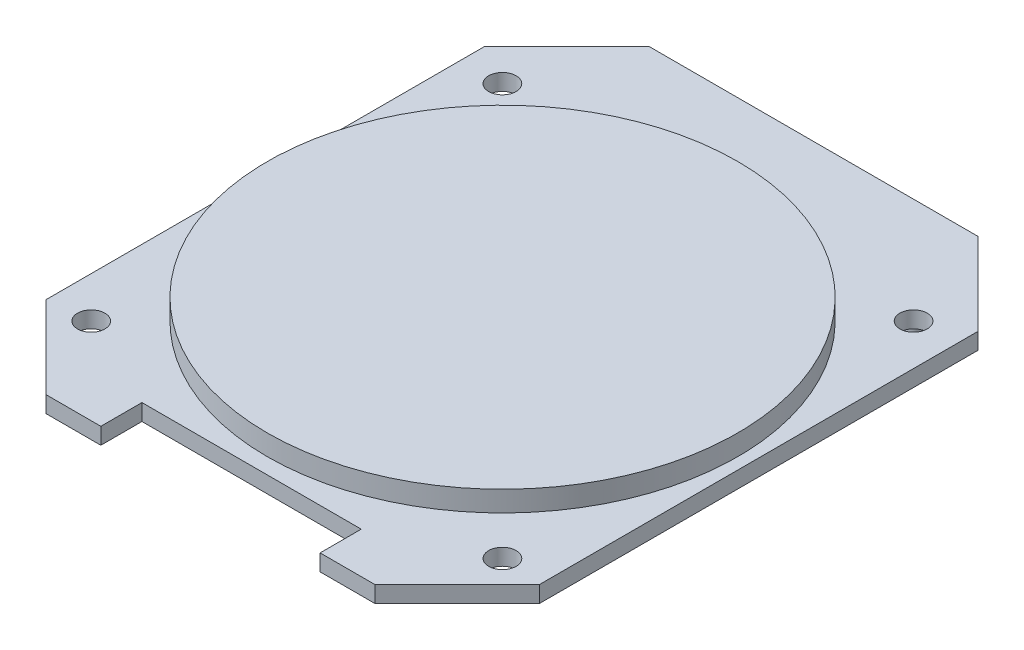
SolidWorks part; units mm, degrees
ref_plane "前视基准面" through (0, 0, 0) normal (0, 0, 1) x (1, 0, 0)
ref_plane "上视基准面" through (0, 0, 0) normal (0, 1, 0) x (1, 0, 0)
ref_plane "右视基准面" through (0, 0, 0) normal (1, 0, 0) x (0, 0, -1)
sketch "草图1" plane through (0, 0, 0) normal (0, 1, 0) x (1, 0, 0)
  line L0 (0, 0) -> (0, 34.4262) construction
  line L1 (-12, 44) -> (12, 44)
  line L2 (12, 44) -> (18, 38)
  line L3 (18, 38) -> (18, 6)
  line L4 (18, 6) -> (12, 0)
  line L5 (12, 0) -> (8, 0)
  line L6 (8, 0) -> (8, 3)
  line L7 (8, 3) -> (-8, 3)
  line L8 (15, 6.3) -> (15, 57.1325) construction
  line L9 (-8, 0) -> (-8, 3)
  line L10 (-12, 0) -> (-8, 0)
  line L11 (-18, 6) -> (-12, 0)
  line L12 (-18, 38) -> (-18, 6)
  line L13 (-12, 44) -> (-18, 38)
  circle A0 centre (15, 6.3) radius 1
  circle A1 centre (15, 36.3) radius 1
  circle A2 centre (-15, 6.3) radius 1
  circle A3 centre (-15, 36.3) radius 1
  point P3 (15, 36.3)
  point P15 (0, 0)
  point P19 (0, 3)
  point P28 (0, 44)
  dimension "D8" = 2
  dimension "D9" = 3
  dimension "D12" = 2
  dimension "D1" = 18
  dimension "D2" = 44
  dimension "D3" = 6
  dimension "D4" = 45
  dimension "D5" = 45
  dimension "D6" = 3
  dimension "D7" = 4
  dimension "D10" = 6.3
  dimension "D11" = 7.7
extrude "凸台-拉伸1" add sketch "草图1" along normal blind 1.2
sketch "草图2" plane through (0, 1.2, 0) normal (0, 1, 0) x (1, 0, 0)
  line L0 (18, 21.31) -> (-18, 21.31) construction
  line L4 (12, 44) -> (-12, 44) construction
  line L5 (0, 0) -> (0, 45.8273) construction
  circle A0 centre (0, 21.31) radius 17.16
  dimension "D1" = 34.32
  dimension "D2" = 22.69
extrude "凸台-拉伸2" add sketch "草图2" along normal blind 1.5
sketch "草图3" plane through (0, 0, 0) normal (0, -1, 0) x (1, 0, 0)
  line L0 (0, -44) -> (0, 0) construction
  line L1 (6, -32.5) -> (-6, -32.5)
  line L2 (6, -32.5) -> (6, -28)
  line L3 (6, -28) -> (-6, -28)
  line L5 (12, -44) -> (-12, -44) construction
  line L6 (-6, -32.5) -> (-6, -28)
  line L7 (-8, -3) -> (8, -3) construction
  line L8 (-11.43, -44) -> (-11.43, -41.46)
  line L9 (11.43, -44) -> (-11.43, -44)
  line L10 (11.43, -44) -> (11.43, -41.46)
  line L11 (11.43, -41.46) -> (-11.43, -41.46)
  point P11 (0, -28)
  point P12 (0, -32.5)
  point P18 (0, -41.46)
  point P19 (0, -44)
  dimension "D1" = 4.5
  dimension "D2" = 25
  dimension "D3" = 12
  dimension "D4" = 2.54
  dimension "D5" = 22.86
extrude "凸台-拉伸3" add sketch "草图3" along normal blind 2
sketch "草图4" plane through (0, 0, 0) normal (0, -1, 0) x (1, 0, 0)
  line L0 (0, 0) -> (0, -45.8273) construction
  line L1 (11.1109, -42.5) -> (-17.9409, -42.5) construction
  line L2 (12, -44) -> (11.43, -44) construction
  circle A0 centre (-1.27, -42.5) radius 0.5
  circle A1 centre (-3.81, -42.5) radius 0.5
  circle A2 centre (-6.35, -42.5) radius 0.5
  circle A3 centre (-8.89, -42.5) radius 0.5
  circle A4 centre (8.89, -42.5) radius 0.5
  circle A5 centre (6.35, -42.5) radius 0.5
  circle A6 centre (3.81, -42.5) radius 0.5
  circle A7 centre (1.27, -42.5) radius 0.5
  dimension "D1" = 2.54
  dimension "D2" = 2.54
  dimension "D3" = 2.54
  dimension "D5" = 1
  dimension "D6" = 1
  dimension "D7" = 1
  dimension "D8" = 1
  dimension "D4" = 1.27
  dimension "D9" = 1.5
extrude "凸台-拉伸4" add sketch "草图4" along normal blind 8
sketch "草图5" plane through (0, 2.7, 0) normal (0, 1, 0) x (1, 0, 0)
  text T0 "<b>Smart Knob</b>\r\n<b>  Simple</b>"
